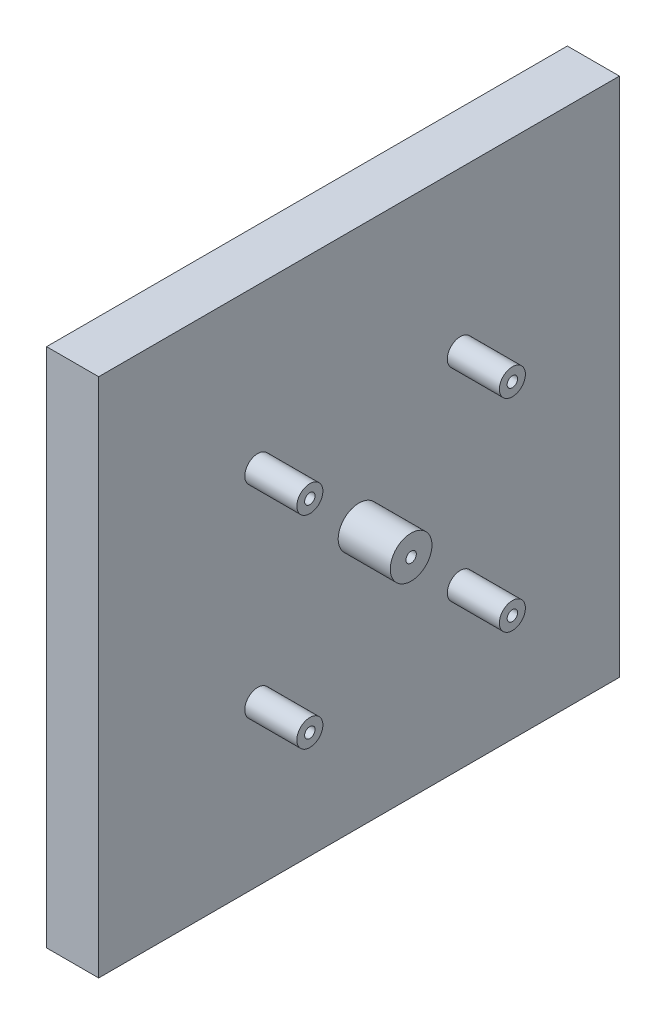
SolidWorks part; units mm, degrees
ref_plane "Front Plane" through (0, 0, 0) normal (0, 0, 1) x (1, 0, 0)
ref_plane "Top Plane" through (0, 0, 0) normal (0, 1, 0) x (1, 0, 0)
ref_plane "Right Plane" through (0, 0, 0) normal (1, 0, 0) x (0, 0, -1)
sketch "Sketch1" plane through (0, 0, 0) normal (1, 0, 0) x (0, 0, -1)
  line L0 (-76.29, 0) -> (76.29, 0) construction
  line L1 (0, 76.29) -> (0, -76.29) construction
  line L2 (-50, 50) -> (-50, -50)
  line L3 (-50, -50) -> (50, -50)
  line L4 (50, -50) -> (50, 50)
  line L5 (50, 50) -> (-50, 50)
  line L6 (-50, -50) -> (50, 50) construction
  line L7 (-50, 50) -> (50, -50) construction
  circle A0 centre (19.4454, 19.4454) radius 1
  circle A1 centre (19.4454, 19.4454) radius 2.5 construction
  circle A2 centre (19.4454, -19.4454) radius 1
  circle A3 centre (19.4454, -19.4454) radius 2.5 construction
  circle A4 centre (-19.4454, -19.4454) radius 1
  circle A5 centre (0, 0) radius 4 construction
  circle A6 centre (-19.4454, -19.4454) radius 2.5 construction
  circle A7 centre (-19.4454, 19.4454) radius 1
  circle A8 centre (0, 0) radius 1
  circle A9 centre (-19.4454, 19.4454) radius 2.5 construction
  point P8 (0, 0)
  point P10 (0, 0)
  point P11 (0, 0)
  point P15 (0, -0.9221)
  point P29 (0, 0)
  dimension "D1" = 100
  dimension "D2" = 4
  dimension "D5" = 100
  dimension "D3" = 55
extrude "Boss-Extrude2" add sketch "Sketch1" along normal blind 10
sketch "Sketch2" plane through (10, 0, 0) normal (1, 0, 0) x (0, 0, -1)
  circle A0 centre (19.4454, 19.4454) radius 1
  circle A3 centre (0, 0) radius 4
  circle A4 centre (19.4454, 19.4454) radius 2.5
  circle A5 centre (19.4454, -19.4454) radius 1
  circle A6 centre (19.4454, -19.4454) radius 2.5
  circle A7 centre (-19.4454, -19.4454) radius 1
  circle A8 centre (-19.4454, -19.4454) radius 2.5
  circle A9 centre (-19.4454, 19.4454) radius 1
  circle A10 centre (-19.4454, 19.4454) radius 2.5
  circle A11 centre (0, 0) radius 1
  point P22 (0, 0)
  point P25 (0, 0)
  dimension "D1" = 4
extrude "Boss-Extrude3" add sketch "Sketch2" along normal blind 10
